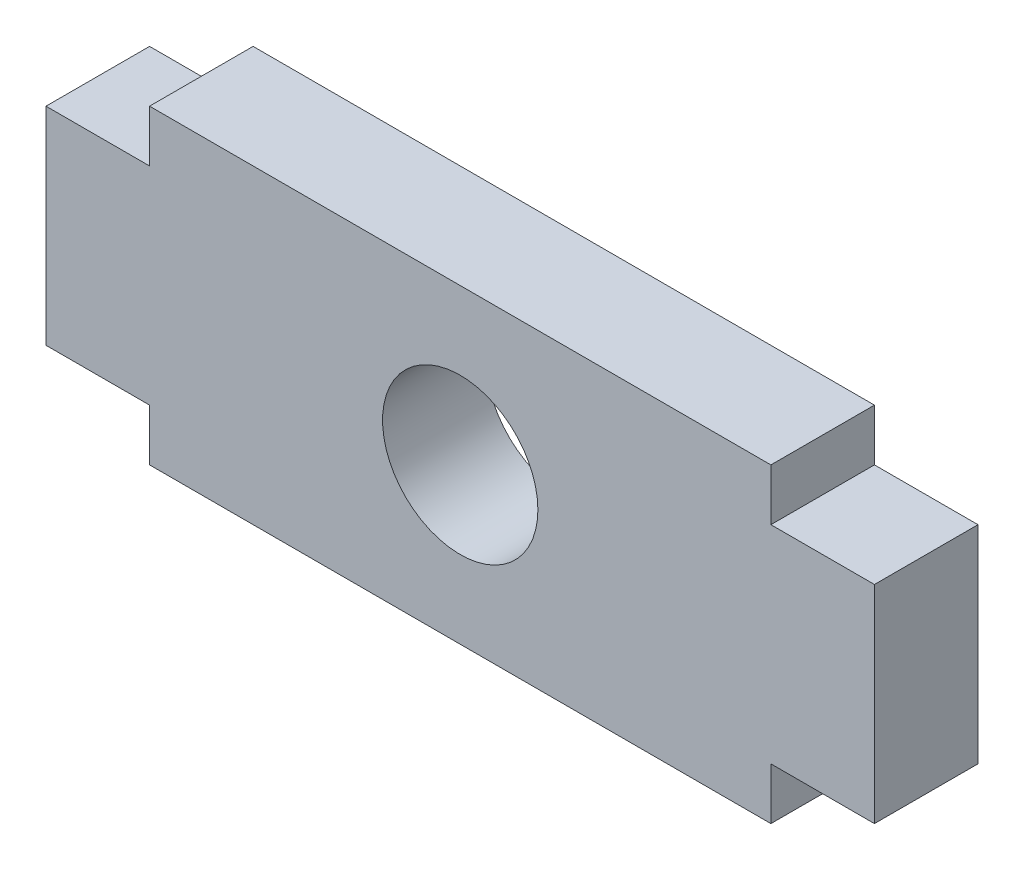
SolidWorks part; units mm, degrees
ref_plane "Front Plane" through (0, 0, 0) normal (0, 0, 1) x (1, 0, 0)
ref_plane "Top Plane" through (0, 0, 0) normal (0, 1, 0) x (1, 0, 0)
ref_plane "Right Plane" through (0, 0, 0) normal (1, 0, 0) x (0, 0, -1)
sketch "Sketch1" plane through (0, 0, 0) normal (0, 0, 1) x (1, 0, 0)
  line L1 (9.525, -4.7625) -> (-9.525, -4.7625)
  line L2 (9.525, -4.7625) -> (9.525, 4.7625)
  line L3 (9.525, 4.7625) -> (-9.525, 4.7625)
  line L4 (-9.525, -4.7625) -> (-9.525, 4.7625)
  line L5 (9.525, -4.7625) -> (-9.525, 4.7625) construction
  line L6 (9.525, 4.7625) -> (-9.525, -4.7625) construction
  line L7 (-9.525, 3.175) -> (-12.7, 3.175)
  line L8 (-9.525, 3.175) -> (-9.525, -3.175)
  line L9 (-9.525, -3.175) -> (-12.7, -3.175)
  line L10 (-12.7, 3.175) -> (-12.7, -3.175)
  line L11 (9.525, -3.175) -> (12.7, -3.175)
  line L12 (9.525, -3.175) -> (9.525, 3.175)
  line L13 (9.525, 3.175) -> (12.7, 3.175)
  line L14 (12.7, -3.175) -> (12.7, 3.175)
  circle A0 centre (0, 0) radius 2.3813
  point P0 (0, 0)
  dimension "D3" = 4.7625
  dimension "D1" = 19.05
  dimension "D2" = 9.525
  dimension "D4" = 3.175
  dimension "D5" = 3.175
  dimension "D6" = 6.35
  dimension "D7" = 6.35
  dimension "D8" = 1.5875
  dimension "D9" = 1.5875
extrude "Boss-Extrude1" add sketch "Sketch1" along normal blind 3.175 contours L7 L10 L9 L4 | L4 L1 L2 L3 A0 | L11 L14 L13 L2
